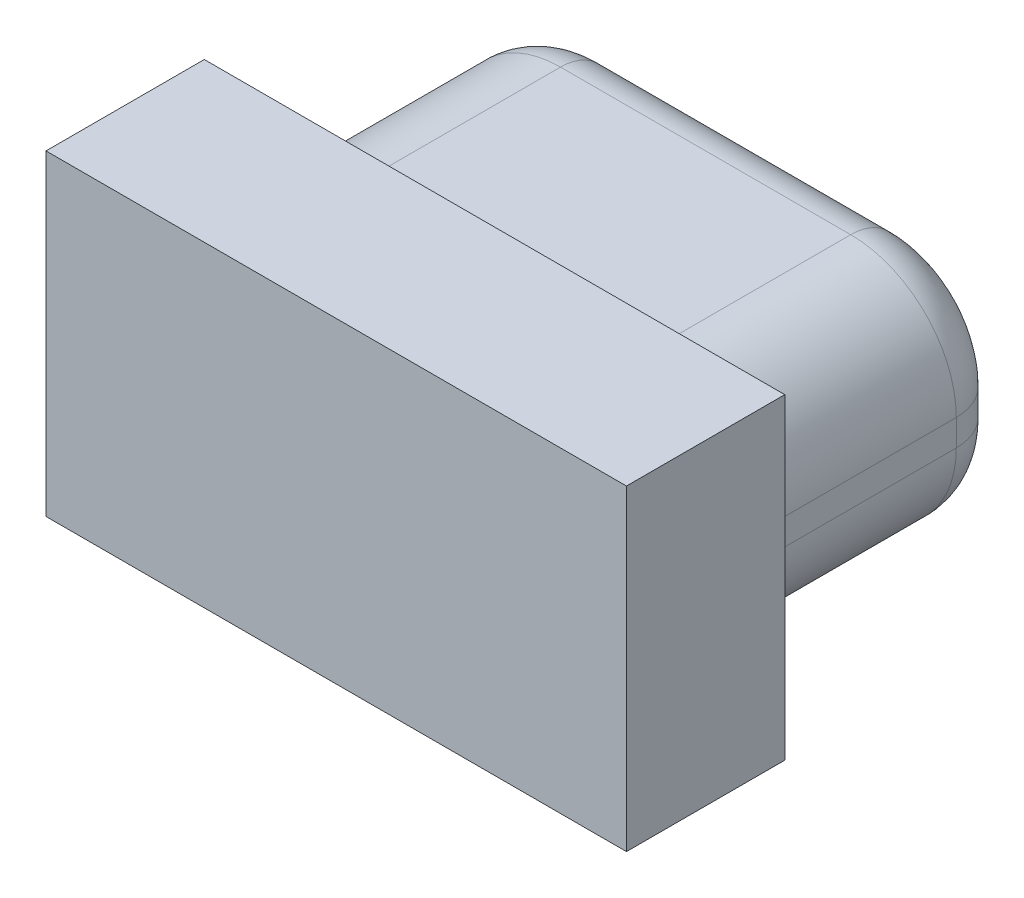
SolidWorks part; units mm, degrees
ref_plane "Front Plane" through (0, 0, 0) normal (0, 0, 1) x (1, 0, 0)
ref_plane "Top Plane" through (0, 0, 0) normal (0, 1, 0) x (1, 0, 0)
ref_plane "Right Plane" through (0, 0, 0) normal (1, 0, 0) x (0, 0, -1)
sketch "Sketch1" plane through (0, 0, 0) normal (0, 0, 1) x (1, 0, 0)
  line L1 (0, 0) -> (9.5, 0)
  line L2 (0, 0) -> (0, 4.5)
  line L3 (0, 4.5) -> (9.5, 4.5)
  line L4 (9.5, 0) -> (9.5, 4.5)
  dimension "D1" = 4.5
  dimension "D2" = 9.5
extrude "Boss-Extrude1" add sketch "Sketch1" along normal blind 5
sketch "Sketch2" plane through (0, 0, 5) normal (0, 0, 1) x (1, 0, 0)
  line L0 (0, 4.5) -> (0, 0) construction
  line L1 (-0.75, 5.25) -> (10.25, 5.25)
  line L2 (-0.75, 5.25) -> (-0.75, -0.75)
  line L3 (-0.75, -0.75) -> (10.25, -0.75)
  line L4 (10.25, 5.25) -> (10.25, -0.75)
  line L5 (9.5, 4.5) -> (0, 4.5) construction
  dimension "D1" = 6
  dimension "D2" = 11
  dimension "D3" = 0.75
  dimension "D4" = 0.75
extrude "Boss-Extrude2" add sketch "Sketch2" along normal blind 3
fillet "Fillet1" radius 2 4 edges at (0, 4.5, 2.5) (9.5, 4.5, 2.5) (9.5, 0, 2.5) (0, 0, 2.5)
fillet "Fillet2" radius 1 8 edges at (0.5858, 0.5858, 0) (0, 2.25, 0) (0.5858, 3.9142, 0) (4.75, 4.5, 0) (8.9142, 3.9142, 0) (9.5, 2.25, 0) (8.9142, 0.5858, 0) (4.75, 0, 0)
